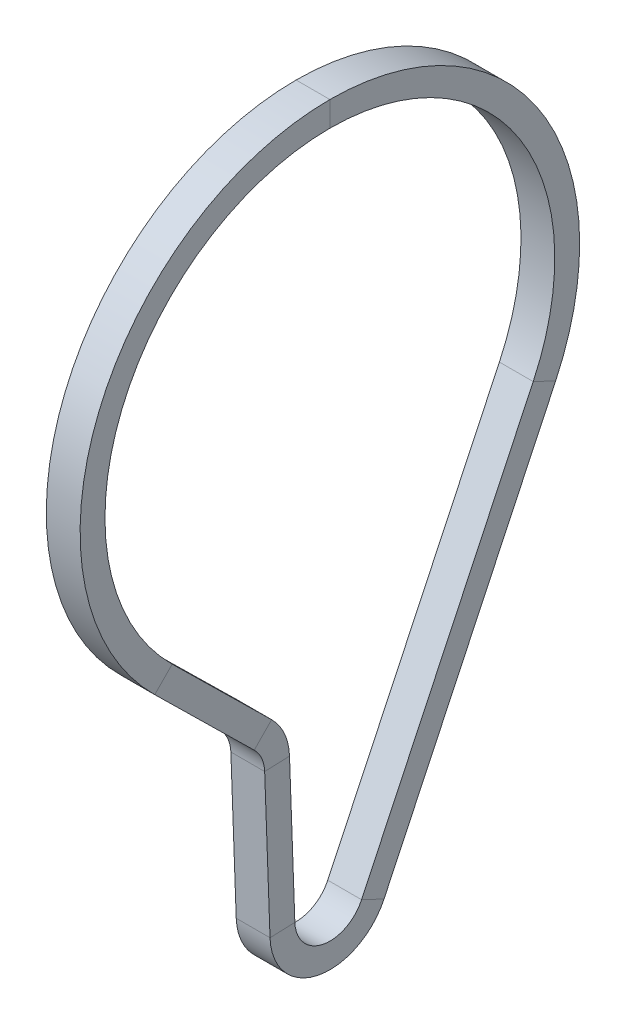
SolidWorks part; units mm, degrees
material "6061-T6 (SS)"
ref_plane "Front Plane" through (0, 0, 0) normal (0, 0, 1) x (1, 0, 0)
ref_plane "Top Plane" through (0, 0, 0) normal (0, 1, 0) x (1, 0, 0)
ref_plane "Right Plane" through (0, 0, 0) normal (1, 0, 0) x (0, 0, -1)
sketch "Sketch1" plane through (0, 0, 0) normal (1, 0, 0) x (0, 0, -1)
  line L0 (16.4446, -177.9583) -> (82.2231, -38.8915)
  line L1 (-18.1793, -170.8434) -> (-20.2301, -114.6423)
  line L2 (-25.6553, -102.3342) -> (-63.7707, -64.8574)
  line L3 (0, 0) -> (0, -170.18) construction
  line L4 (0, -99.3646) -> (-72.5573, -129.4782) construction
  line L5 (-82.2231, -38.8915) -> (-16.4446, -177.9583) construction
  arc A0 (82.2231, -38.8915) -> (-63.7707, -64.8574) centre (0, 0) ccw
  arc A2 (-18.1793, -170.8434) -> (16.4446, -177.9583) centre (0, -170.18) ccw
  arc A3 (-20.2301, -114.6423) -> (-25.6553, -102.3342) centre (-38.4094, -115.3057) ccw
  circle A4 centre (0, 0) radius 90.957 construction
  circle A5 centre (0, -170.18) radius 18.1914 construction
  circle A6 centre (-61.6422, -124.948) radius 18.1914 construction
  dimension "D1" = 181.9141
  dimension "D2" = 36.3828
  dimension "D4" = 170.18
  dimension "D5" = 67.46
  dimension "D6" = 70.8154
sketch "Sketch2" plane through (0, 0, 0) normal (0, 0, 1) x (1, 0, 0)
  line L1 (-6.477, 95.7195) -> (6.477, 95.7195)
  line L2 (-6.477, 95.7195) -> (-6.477, 86.1945)
  line L3 (-6.477, 86.1945) -> (6.477, 86.1945)
  line L4 (6.477, 95.7195) -> (6.477, 86.1945)
  line L5 (-6.477, 95.7195) -> (6.477, 86.1945) construction
  line L6 (-6.477, 86.1945) -> (6.477, 95.7195) construction
  point P0 (0, 90.957)
  dimension "D1" = 12.954
  dimension "D2" = 9.525
sweep "Sweep1" add profiles "Sketch2" path "Sketch1"
sketch "Chain Removal Sketch" plane through (0, 0, 0) normal (1, 0, 0) x (0, 0, -1)
  line L0 (-83.1894, -36.7792) -> (-20.2523, -179.1338)
  line L1 (83.1894, -36.7792) -> (20.2523, -179.1338)
  line L2 (15.8965, -177.2081) -> (24.6081, -181.0596) construction
  line L3 (12.1394, -175.9219) -> (20.7498, -179.9946) construction
  circle A0 centre (0, 0) radius 90.957 construction
  circle A1 centre (0, -170.18) radius 22.1433 construction
  arc A2 (83.1894, -36.7792) -> (-83.1894, -36.7792) centre (0, 0) ccw
  arc A3 (-20.2523, -179.1338) -> (20.2523, -179.1338) centre (0, -170.18) ccw
  circle A4 centre (0, -170.18) radius 20.6375
  circle A5 centre (0, 0) radius 90.957 construction
sketch "Sketch4" plane through (6.477, 0, 0) normal (1, 0, 0) x (0, 0, -1)
  line L0 (0, -192.3415) -> (0, -201.8665) construction
  line L1 (12.1394, -175.9219) -> (20.7498, -179.9946) construction
  circle A0 centre (0, -170.18) radius 31.6865
  circle A1 centre (0, -170.18) radius 22.1615
  circle A2 centre (0, -170.18) radius 20.6375 construction
  dimension "D1" = 1.524
extrude "Boss-Extrude1" [suppressed] add sketch "Sketch4" against normal up to vertex separate body
sketch "Sketch5" plane through (0, 0, 0) normal (1, 0, 0) x (0, 0, -1)
  line L0 (0, 0) -> (1.3893, -38.0747) construction
  line L1 (0, 0) -> (27.1674, -26.7122) construction
  line L2 (-22.9386, -171.017) -> (-24.9894, -114.816) construction
  line L3 (-28.9943, -105.7301) -> (-67.1097, -68.2533) construction
  line L4 (27.1674, -26.7122) -> (1.3893, -38.0747) construction
  dimension "D1" = 38.1
  dimension "D2" = 28.1712
sketch "Sketch6" plane through (0, 0, 0) normal (1, 0, 0) x (0, 0, -1)
  line L0 (16.4446, -177.9583) -> (82.2231, -38.8915) construction
  line L1 (16.4446, -177.9583) -> (82.2231, -38.8915)
  line L2 (-17.9812, -167.4224) -> (-9.7306, -113.6234)
  line L3 (-18.2708, -95.316) -> (-47.2048, -77.7489)
  line L5 (0, -99.3646) -> (-72.5573, -129.4782) construction
  line L6 (0, 0) -> (-10.6941, 0) construction
  arc A0 (-18.1793, -170.8434) -> (16.4446, -177.9583) centre (0, -170.18) ccw construction
  arc A1 (82.2231, -38.8915) -> (-63.7707, -64.8574) centre (0, 0) ccw construction
  arc A2 (-17.9812, -167.4224) -> (16.4446, -177.9583) centre (0, -170.18) ccw
  arc A3 (82.2231, -38.8915) -> (-47.2048, -77.7489) centre (0, 0) ccw
  circle A4 centre (0, -170.18) radius 18.1914 construction
  arc A5 (-9.7306, -113.6234) -> (-18.2708, -95.316) centre (-27.7118, -110.8658) ccw
  arc A6 (-20.2301, -114.6423) -> (-25.6553, -102.3342) centre (-38.4094, -115.3057) ccw construction
  dimension "D1" = 11.5824
  dimension "D3" = 10.6941
equation "\"D1@Sketch1\"=.375*60/pi"
equation "\"D2@Sketch1\"=12*.375/pi"
equation "\"D1@Chain Removal Sketch\" = \"D3@Sketch1\""
equation "\"D3@Sketch6\"=\"D2@Sketch6\"-\"D3@sketch1\""
